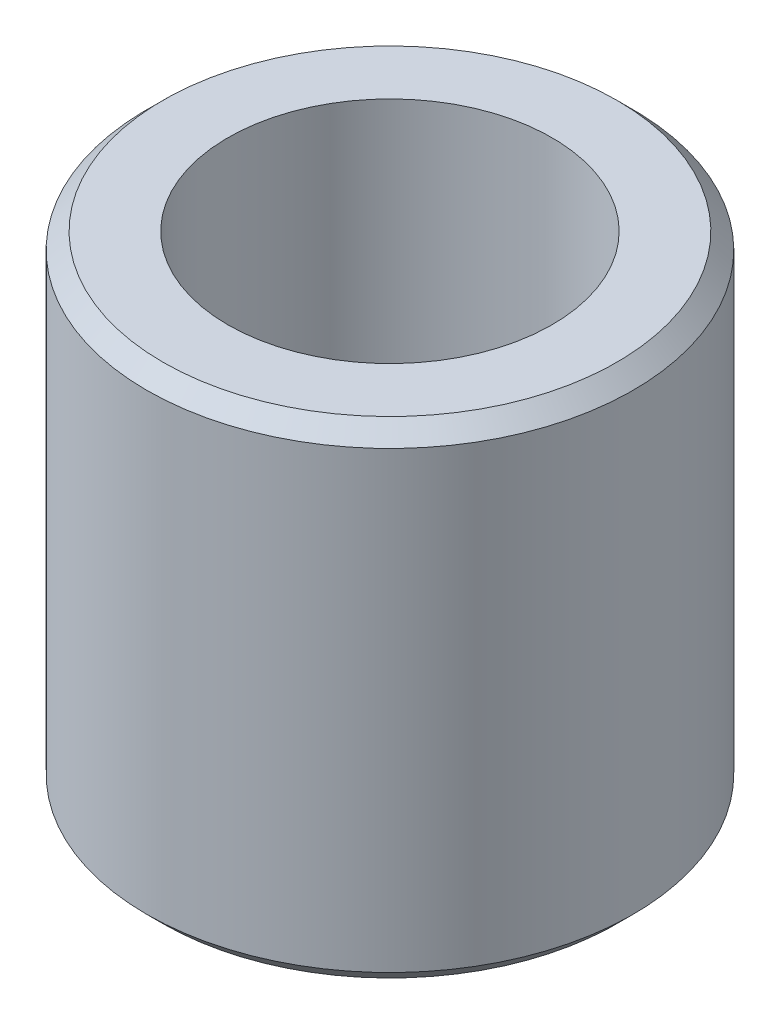
SolidWorks part; units mm, degrees
material "Copper"
ref_plane "Front Plane" through (0, 0, 0) normal (0, 0, 1) x (1, 0, 0)
ref_plane "Top Plane" through (0, 0, 0) normal (0, 1, 0) x (1, 0, 0)
ref_plane "Right Plane" through (0, 0, 0) normal (1, 0, 0) x (0, 0, -1)
sketch "Sketch1" plane through (0, 0, 0) normal (0, 1, 0) x (1, 0, 0)
  circle A0 centre (0, 0) radius 10
  circle A1 centre (0, 0) radius 15
  dimension "D1" = 30
  dimension "D2" = 20
extrude "Boss-Extrude1" add sketch "Sketch1" along normal blind 30
chamfer "Chamfer1" distance 1 angle 45 1 edges at (0, 0, 15)
chamfer "Chamfer2" distance 1 angle 45 1 edges at (0, 30, 15)
